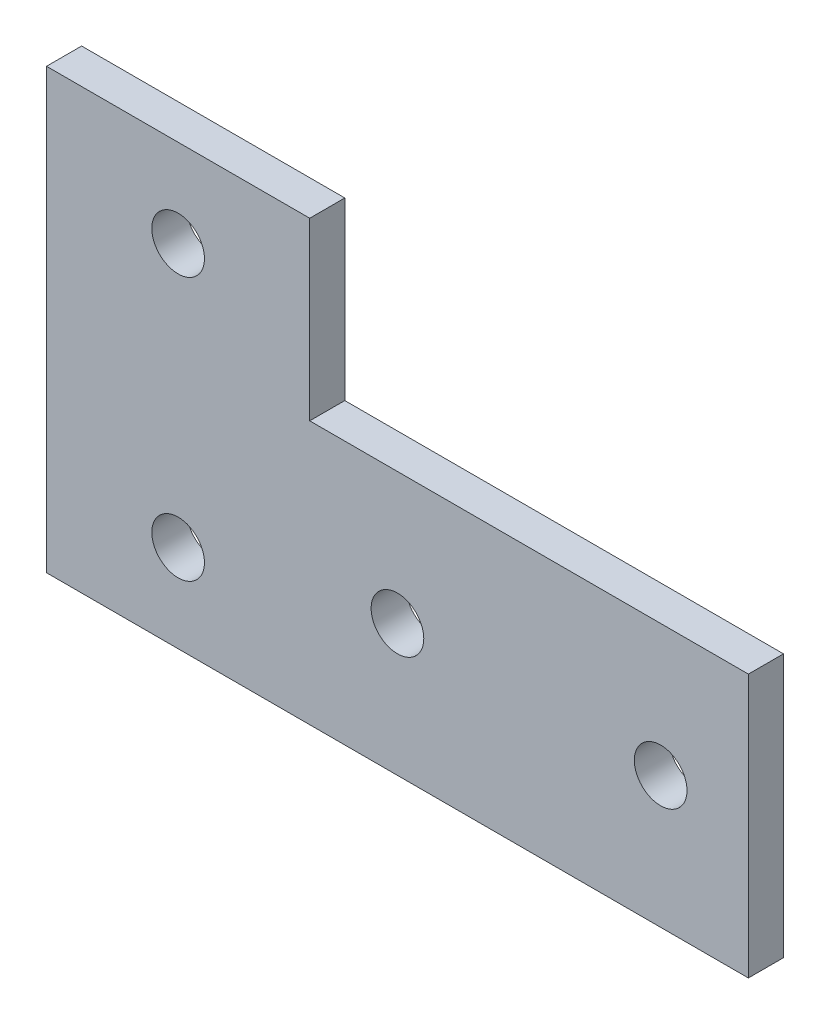
SolidWorks part; units mm, degrees
ref_plane "Plan de face" through (0, 0, 0) normal (0, 0, 1) x (1, 0, 0)
ref_plane "Plan de dessus" through (0, 0, 0) normal (0, 1, 0) x (1, 0, 0)
ref_plane "Plan de droite" through (0, 0, 0) normal (1, 0, 0) x (0, 0, -1)
sketch "Esquisse1" plane through (0, 0, 0) normal (0, 0, 1) x (1, 0, 0)
  line L1 (0, 0) -> (15, 0)
  line L2 (0, 0) -> (0, 25)
  line L3 (0, 25) -> (15, 25)
  line L4 (15, 15) -> (15, 25)
  line L5 (15, 0) -> (40, 0)
  line L7 (15, 15) -> (40, 15)
  line L8 (40, 0) -> (40, 15)
  dimension "D1" = 15
  dimension "D2" = 15
  dimension "D3" = 25
  dimension "D4" = 25
extrude "Extrusion1" add sketch "Esquisse1" along normal blind 2
sketch "Esquisse2" plane through (0, 0, 2) normal (0, 0, 1) x (1, 0, 0)
  line L0 (0, 25) -> (0, 0) construction
  line L1 (15, 25) -> (0, 25) construction
  line L2 (0, 0) -> (40, 0) construction
  line L3 (40, 15) -> (15, 15) construction
  line L4 (40, 0) -> (40, 15) construction
  circle A0 centre (7.5, 20) radius 1.5
  circle A1 centre (7.5, 5) radius 1.5
  circle A2 centre (20, 7.5) radius 1.5
  circle A3 centre (35, 7.5) radius 1.5
  dimension "D1" = 3
  dimension "D2" = 3
  dimension "D3" = 3
  dimension "D4" = 3
  dimension "D6" = 5
  dimension "D7" = 5
  dimension "D9" = 7.5
  dimension "D10" = 7.5
  dimension "D11" = 20
  dimension "D5" = 7.5
  dimension "D8" = 7.5
  dimension "D12" = 5
extrude "Extrusion2" cut sketch "Esquisse2" against normal through all
